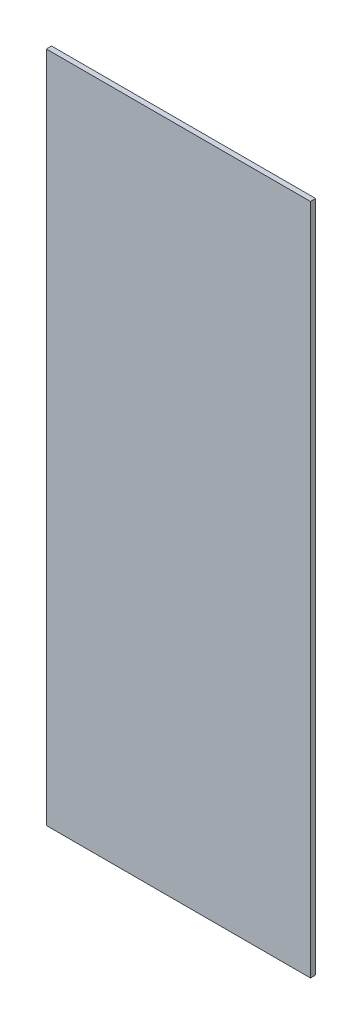
SolidWorks part; units mm, degrees
material "Pine"
ref_plane "Front Plane" through (0, 0, 0) normal (0, 0, 1) x (1, 0, 0)
ref_plane "Top Plane" through (0, 0, 0) normal (0, 1, 0) x (1, 0, 0)
ref_plane "Right Plane" through (0, 0, 0) normal (1, 0, 0) x (0, 0, -1)
sketch "Sketch1" plane through (0, 0, 0) normal (0, 0, 1) x (1, 0, 0)
  line L1 (-324, -825) -> (324, -825)
  line L2 (-324, -825) -> (-324, 825)
  line L3 (-324, 825) -> (324, 825)
  line L4 (324, -825) -> (324, 825)
  line L5 (-324, -825) -> (324, 825) construction
  line L6 (-324, 825) -> (324, -825) construction
  point P0 (0, 0)
  dimension "D1" = 648
  dimension "D2" = 1650
extrude "Boss-Extrude1" add sketch "Sketch1" along normal blind 12.7
